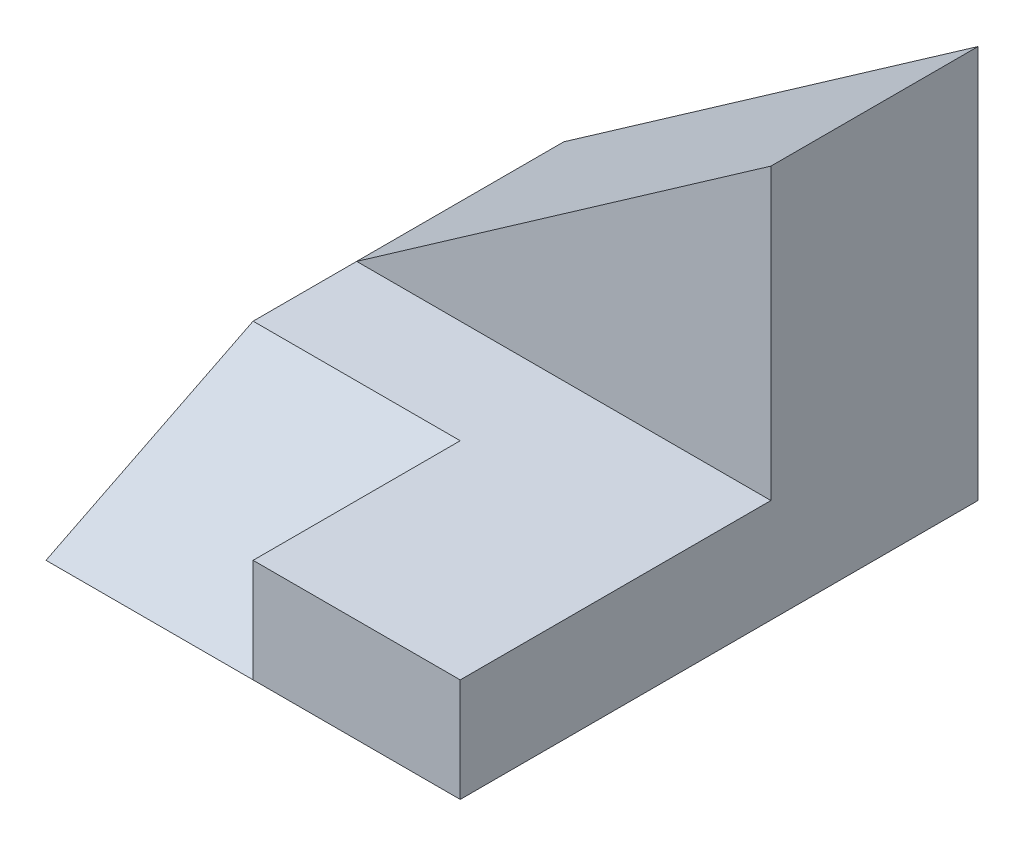
SolidWorks part; units mm, degrees
ref_plane "Front Plane" through (0, 0, 0) normal (0, 0, 1) x (1, 0, 0)
ref_plane "Top Plane" through (0, 0, 0) normal (0, 1, 0) x (1, 0, 0)
ref_plane "Right Plane" through (0, 0, 0) normal (1, 0, 0) x (0, 0, -1)
sketch "Sketch1" plane through (0, 0, 0) normal (0, 0, 1) x (1, 0, 0)
  line L0 (0, 10) -> (40, 37.9669)
  line L1 (0, 0) -> (40, 0)
  line L2 (0, 0) -> (0, 10)
  line L4 (40, 0) -> (40, 10)
  line L5 (40, 37.9669) -> (40, 10)
  dimension "D1" = 40
  dimension "D2" = 10
extrude "Boss-Extrude1" add sketch "Sketch1" along normal blind 20
sketch "Sketch3" plane through (0, 0, 20) normal (0, 0, 1) x (1, 0, 0)
  line L0 (40, 0) -> (40, 37.9669) construction
  line L1 (0, 10) -> (40, 10)
  line L2 (0, 10) -> (0, 0)
  line L3 (0, 0) -> (40, 0)
  line L4 (40, 10) -> (40, 0)
extrude "Boss-Extrude2" add sketch "Sketch3" along normal blind 30
sketch "Sketch4" plane through (0, 0, 0) normal (-1, 0, 0) x (0, 0, 1)
  line L0 (50, 10) -> (30, 10)
  line L2 (50, 0) -> (50, 10)
  line L3 (50, 10) -> (20, 10) construction
  line L4 (30, 10) -> (50, 0)
  dimension "D1" = 20
extrude "Cut-Extrude2" cut sketch "Sketch4" against normal blind 20
